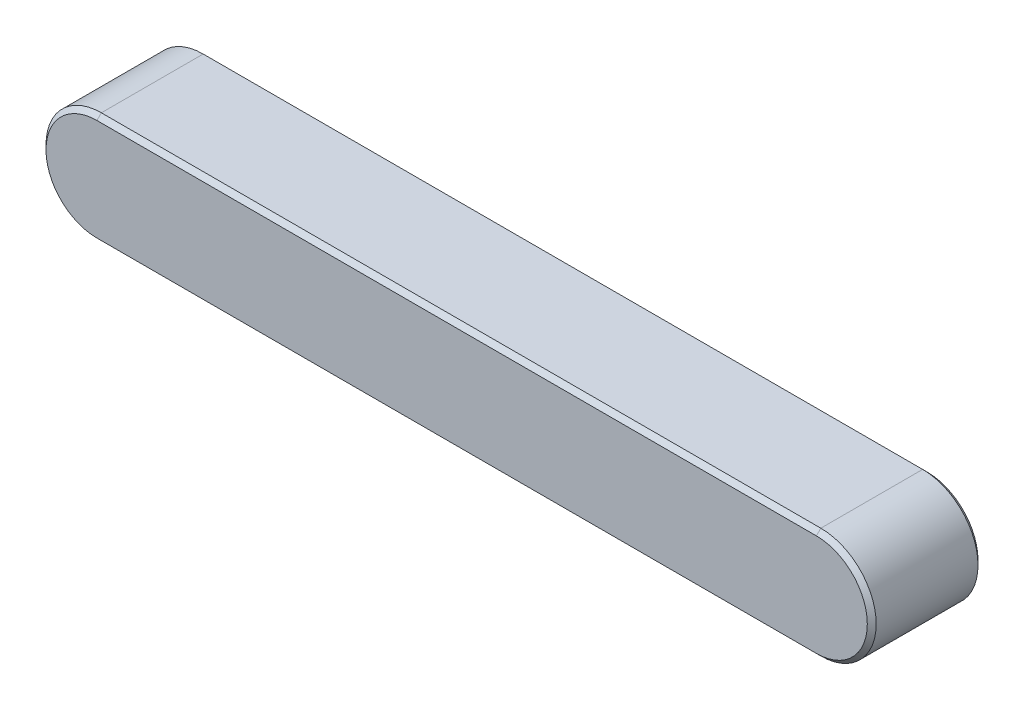
SolidWorks part; units mm, degrees
ref_plane "前视基准面" through (0, 0, 0) normal (0, 0, 1) x (1, 0, 0)
ref_plane "上视基准面" through (0, 0, 0) normal (0, 1, 0) x (1, 0, 0)
ref_plane "右视基准面" through (0, 0, 0) normal (1, 0, 0) x (0, 0, -1)
sketch "草图1" plane through (0, 0, 0) normal (0, 0, 1) x (1, 0, 0)
  line L0 (-13, 0) -> (13, 0) construction
  line L1 (-13, 2) -> (13, 2)
  line L2 (-13, -2) -> (13, -2)
  arc A0 (-13, 2) -> (-13, -2) centre (-13, 0) ccw
  arc A1 (13, -2) -> (13, 2) centre (13, 0) ccw
  point P2 (0, 0)
  dimension "D1" = 4
  dimension "D2" = 26
extrude "凸台-拉伸1" add sketch "草图1" along normal blind 4
chamfer "倒角1" distance 0.16 angle 45 8 edges at (0, 2, 4) (-15, 0, 4) (15, 0, 4) (0, -2, 4) (0, 2, 0) (-15, 0, 0) (15, 0, 0) (0, -2, 0)
